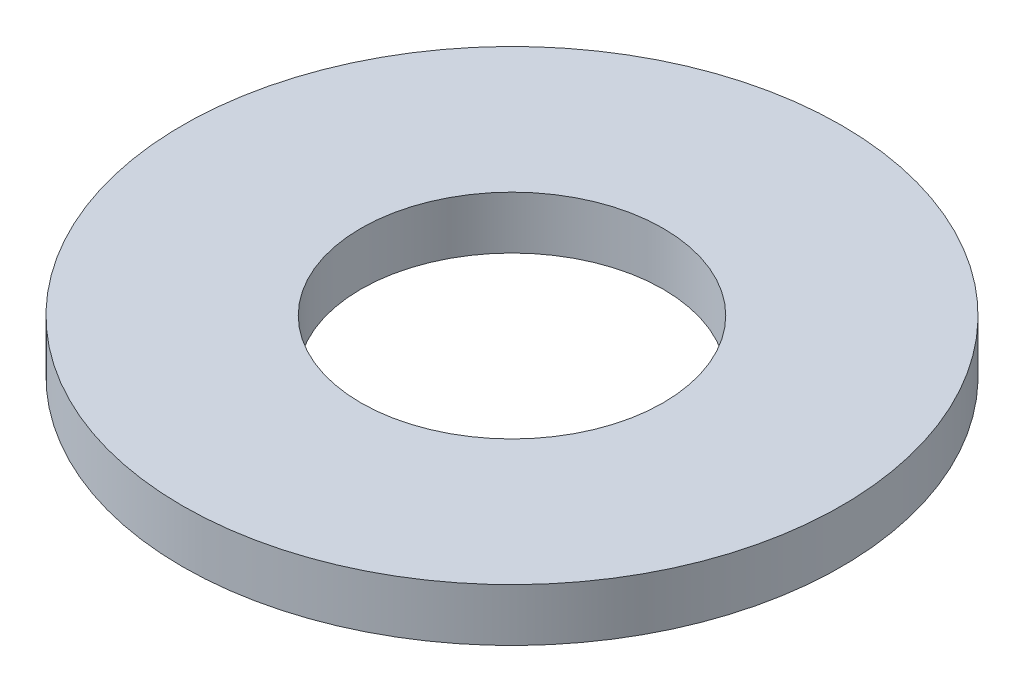
SolidWorks part; units mm, degrees
ref_plane "Front Plane" through (0, 0, 0) normal (0, 0, 1) x (1, 0, 0)
ref_plane "Top Plane" through (0, 0, 0) normal (0, 1, 0) x (1, 0, 0)
ref_plane "Right Plane" through (0, 0, 0) normal (1, 0, 0) x (0, 0, -1)
sketch "Sketch1" plane through (0, 0, 0) normal (0, 1, 0) x (1, 0, 0)
  circle A0 centre (0, 0) radius 9.525
  dimension "OD" = 19.05
extrude "Boss-Extrude1" add sketch "Sketch1" along normal blind 1.524
sketch "Sketch5" plane through (0, 1.524, 0) normal (0, 1, 0) x (-1, 0, 0)
  circle A0 centre (0, 0) radius 4.3688
  dimension "ID" = 8.7376
extrude "Cut-Extrude1" cut sketch "Sketch5" against normal through all
